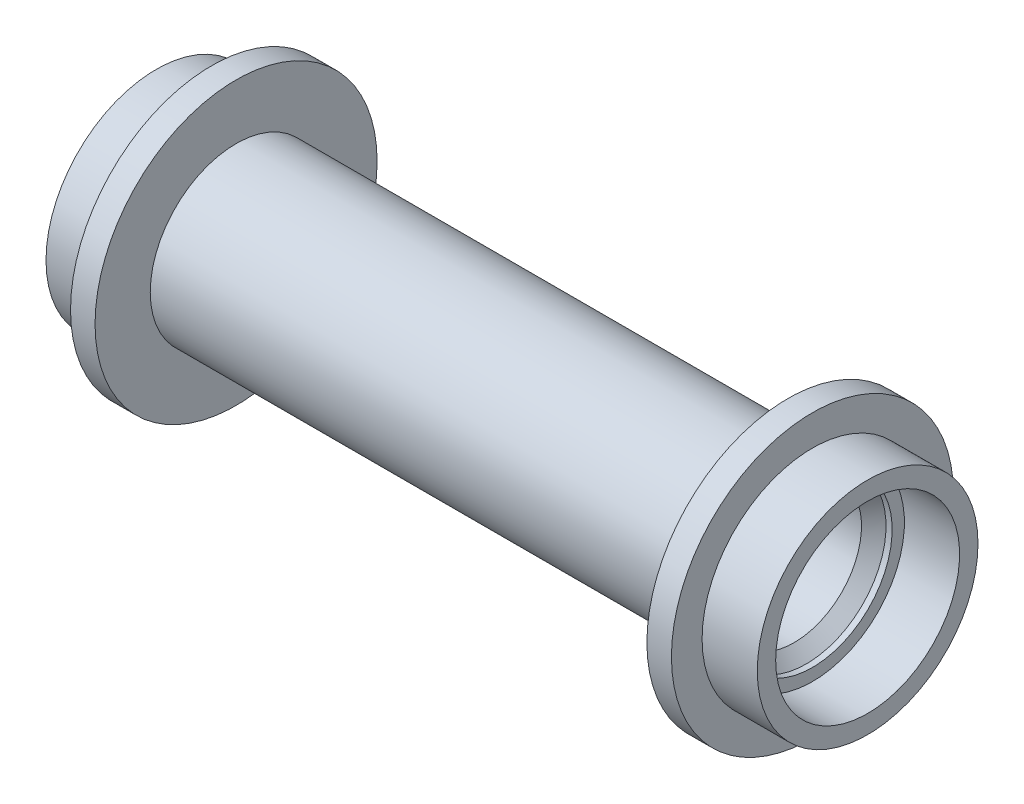
SolidWorks part; units mm, degrees
material "POM 乙缩醛共聚物"
ref_plane "前视基准面" through (0, 0, 0) normal (0, 0, 1) x (1, 0, 0)
ref_plane "上视基准面" through (0, 0, 0) normal (0, 1, 0) x (1, 0, 0)
ref_plane "右视基准面" through (0, 0, 0) normal (1, 0, 0) x (0, 0, -1)
sketch "草图1" plane through (0, 0, 0) normal (0, 1, 0) x (1, 0, 0)
  line L0 (0, 0) -> (0, 7) construction
  line L1 (0, 7) -> (22.5, 7)
  line L2 (22.5, 7) -> (22.5, 11.5)
  line L3 (22.5, 11.5) -> (24.5, 11.5)
  line L4 (24.5, 11.5) -> (24.5, 9)
  line L5 (24.5, 9) -> (29, 9)
  line L6 (29, 9) -> (29, 7.5)
  line L7 (29, 7.5) -> (24.5, 7.5)
  line L8 (24.5, 7.5) -> (24.5, 6.5)
  line L9 (24.5, 6.5) -> (24, 6.5)
  line L10 (24, 6.5) -> (23, 5.5)
  line L11 (23, 5.5) -> (0, 5.5)
  line L12 (0, 5.5) -> (0, 7)
  line L13 (0, 0) -> (73.5837, 0) construction
  dimension "D1" = 7
  dimension "D2" = 5.5
  dimension "D3" = 22.5
  dimension "D4" = 11.5
  dimension "D5" = 2
  dimension "D6" = 4.5
  dimension "D7" = 1.5
  dimension "D8" = 9
  dimension "D9" = 6.5
  dimension "D10" = 0.5
  dimension "D11" = 135
revolve "旋转1" add sketch "草图1" angle 360 about L13
mirror "镜向1" about plane through (0, 0, -5.5) normal (1, 0, 0) of "旋转1"
